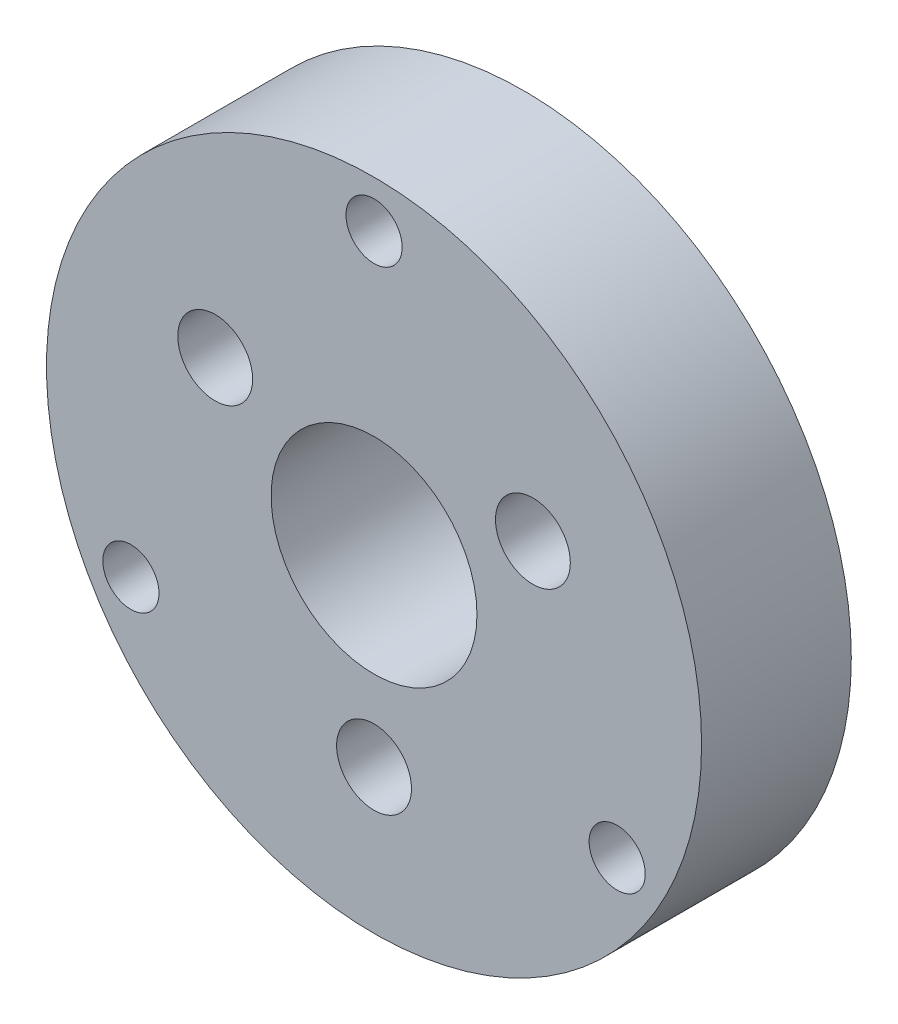
SolidWorks part; units mm, degrees
ref_plane "前视基准面" through (0, 0, 0) normal (0, 0, 1) x (1, 0, 0)
ref_plane "上视基准面" through (0, 0, 0) normal (0, 1, 0) x (1, 0, 0)
ref_plane "右视基准面" through (0, 0, 0) normal (1, 0, 0) x (0, 0, -1)
sketch "草图1" plane through (0, 0, 0) normal (0, 0, 1) x (1, 0, 0)
  circle A0 centre (0, 0) radius 17.5
  circle A1 centre (0, 0) radius 15 construction
  circle A2 centre (0, 15) radius 1.5
  circle A3 centre (12.9904, -7.5) radius 1.5
  circle A4 centre (-12.9904, -7.5) radius 1.5
  circle A5 centre (0, 0) radius 5.5
  point P12 (0, 0)
  dimension "D1" = 35
  dimension "D2" = 30
  dimension "D3" = 3
  dimension "D5" = 11
  dimension "D4" = 3
extrude "凸台-拉伸1" add sketch "草图1" along normal blind 8
sketch "草图2" plane through (0, 0, 0) normal (0, 0, 1) x (1, 0, 0)
  line L0 (0, 21.0688) -> (0, -21.9453) construction
  line L1 (0, 0) -> (-22.3304, 12.8925) construction
  circle A0 centre (0, 0) radius 9.8 construction
  circle A1 centre (-8.487, 4.9) radius 2
  circle A2 centre (8.487, 4.9) radius 2
  circle A3 centre (0, -9.8) radius 2
  point P15 (0, 0)
  dimension "D2" = 19.6
  dimension "D3" = 4
  dimension "D1" = 60
  dimension "D4" = 3
extrude "切除-拉伸1" cut sketch "草图2" along normal blind 19
